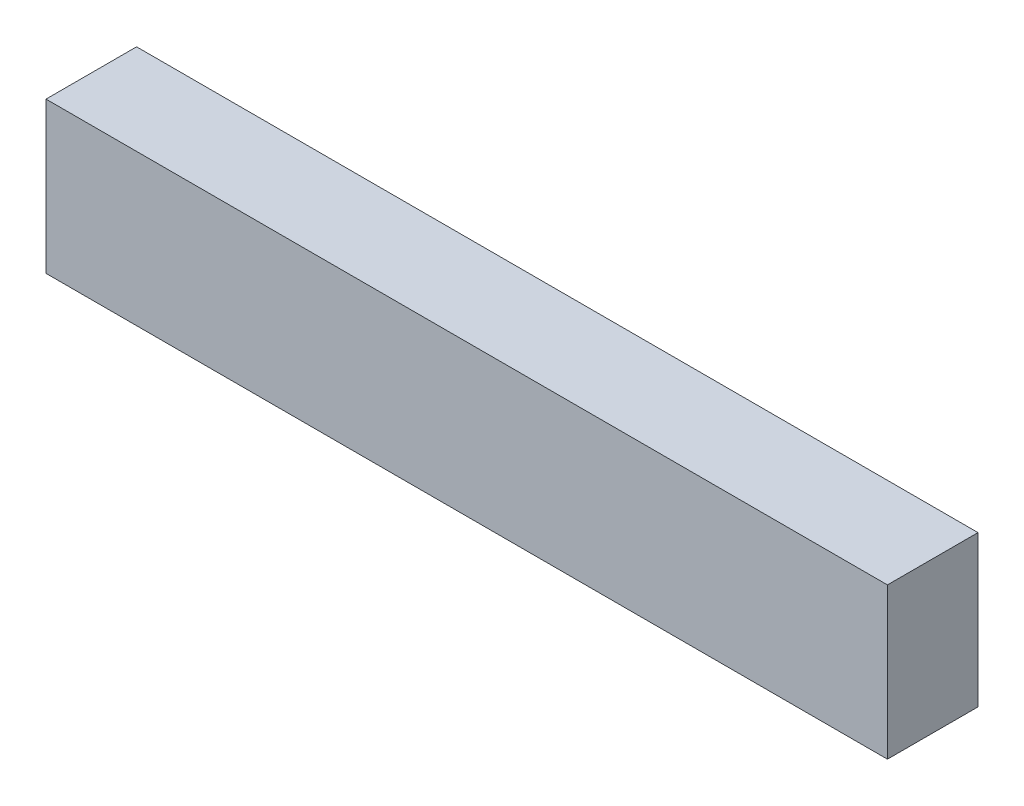
SolidWorks part; units mm, degrees
ref_plane "Front" through (0, 0, 0) normal (0, 0, 1) x (1, 0, 0)
ref_plane "Top" through (0, 0, 0) normal (0, 1, 0) x (1, 0, 0)
ref_plane "Right" through (0, 0, 0) normal (1, 0, 0) x (0, 0, -1)
sketch "Sketch1" plane through (0, 0, 0) normal (0, 0, 1) x (1, 0, 0)
  line L0 (63.5, 63.5) -> (417.45, 63.5) construction
  line L1 (63.5, 127) -> (417.45, 127) construction
  line L2 (417.45, 480.95) -> (417.45, 0) construction
  line L3 (63.5, 480.95) -> (63.5, 0) construction
  line L12 (63.5, 63.5) -> (417.45, 63.5)
  line L13 (63.5, 127) -> (417.45, 127)
  line L14 (417.45, 127) -> (417.45, 63.5)
  line L15 (63.5, 127) -> (63.5, 63.5)
extrude "Boss-Extrude1" add sketch "Sketch1" along normal blind 38.1
